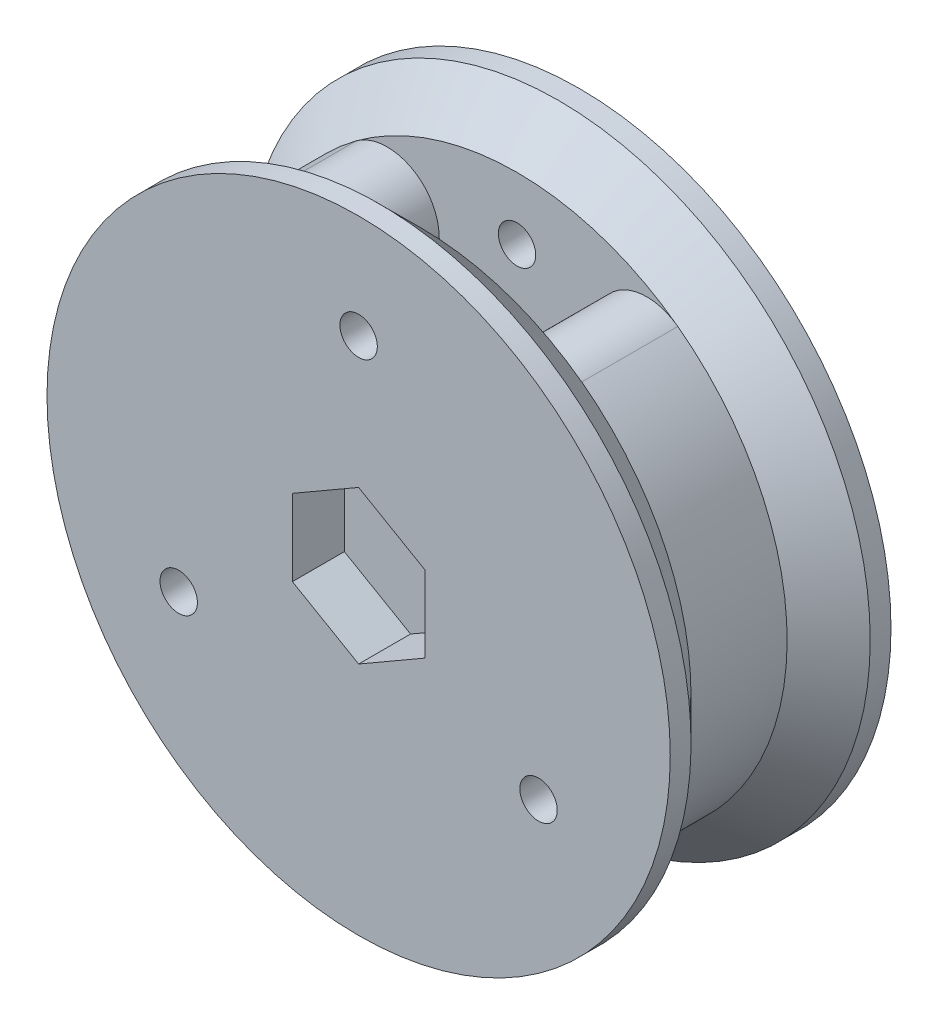
SolidWorks part; units mm, degrees
ref_plane "Front Plane" through (0, 0, 0) normal (0, 0, 1) x (1, 0, 0)
ref_plane "Top Plane" through (0, 0, 0) normal (0, 1, 0) x (1, 0, 0)
ref_plane "Right Plane" through (0, 0, 0) normal (1, 0, 0) x (0, 0, -1)
sketch "Sketch1" plane through (0, 0, 0) normal (0, 0, 1) x (1, 0, 0)
  circle A0 centre (0, 0) radius 30
  dimension "D1" = 60
extrude "Boss-Extrude1" add sketch "Sketch1" along normal blind 21.25
sketch "Sketch2" plane through (0, 0, 21.25) normal (0, 0, 1) x (1, 0, 0)
  line L7 (0, 7.3612) -> (-6.375, 3.6806)
  line L8 (-6.375, 3.6806) -> (-6.375, -3.6806)
  line L9 (-6.375, -3.6806) -> (0, -7.3612)
  line L10 (0, -7.3612) -> (6.375, -3.6806)
  line L11 (6.375, -3.6806) -> (6.375, 3.6806)
  line L12 (6.375, 3.6806) -> (0, 7.3612)
  circle A0 centre (0, 0) radius 6.375 construction
  dimension "D1" = 12.75
extrude "Cut-Extrude1" cut sketch "Sketch2" against normal blind 5
sketch "Sketch4" plane through (0, 0, 0) normal (0, 1, 0) x (1, 0, 0)
  line L0 (30, -19.25) -> (26, -15.25)
  line L1 (30, -21.25) -> (30, 0) construction
  line L2 (26, -15.25) -> (26, -6)
  line L3 (26, -6) -> (30, -2)
  line L4 (30, -2) -> (30, -19.25)
  line L5 (0, 12.6406) -> (0, -40.7984)
  dimension "D1" = 2
  dimension "D2" = 2
  dimension "D3" = 45
  dimension "D4" = 45
  dimension "D5" = 4
revolve "Cut-Revolve1" cut sketch "Sketch4" angle 360 about L5
sketch "Sketch5" plane through (0, 0, 21.25) normal (0, 0, 1) x (1, 0, 0)
  line L0 (0, 0) -> (-17.3205, -10) construction
  line L1 (0, 0) -> (17.3205, -10) construction
  line L2 (0, 0) -> (0, 20) construction
  circle A0 centre (-17.3205, -10) radius 1.8
  circle A2 centre (0, 0) radius 20 construction
  circle A3 centre (17.3205, -10) radius 1.8
  circle A4 centre (0, 20) radius 1.8
  dimension "D1" = 3.6
  dimension "D2" = 40
  dimension "D3" = 120
  dimension "D5" = 3.6
  dimension "D6" = 3.6
  dimension "D4" = 120
extrude "Cut-Extrude2" cut sketch "Sketch5" against normal through all
sketch "Sketch6" plane through (0, 0, 0) normal (0, 0, -1) x (-1, 0, 0)
  line L15 (7.3612, 0) -> (3.6806, 6.375)
  line L16 (3.6806, 6.375) -> (-3.6806, 6.375)
  line L17 (-3.6806, 6.375) -> (-7.3612, 0)
  line L18 (-7.3612, 0) -> (-3.6806, -6.375)
  line L19 (-3.6806, -6.375) -> (3.6806, -6.375)
  line L20 (3.6806, -6.375) -> (7.3612, 0)
  circle A2 centre (0, 0) radius 6.375 construction
  point P1 (0, 6.375)
  dimension "D1" = 12.75
extrude "Cut-Extrude3" cut sketch "Sketch6" against normal blind 13
ref_plane "Plane1" through (0, 40, 0) normal (0, 1, 0) x (1, 0, 0)
sketch "Sketch10" plane through (0, 40, 0) normal (0, 1, 0) x (1, 0, 0)
  line L1 (7.5, -15.25) -> (-7.5, -15.25)
  line L2 (7.5, -15.25) -> (7.5, -6)
  line L3 (7.5, -6) -> (-7.5, -6)
  line L4 (-7.5, -15.25) -> (-7.5, -6)
  line L5 (7.5, -15.25) -> (-7.5, -6) construction
  line L6 (7.5, -6) -> (-7.5, -15.25) construction
  line L8 (-26, -6) -> (26, -6) construction
  line L9 (-26, -15.25) -> (26, -15.25) construction
  point P0 (0, -10.625)
  point P11 (0, -6)
  dimension "D1" = 15
extrude "Cut-Extrude6" cut sketch "Sketch10" against normal blind 28
fillet "Fillet6" radius 5 2 edges at (7.5, 24.8948, 10.625) (-7.5, 24.8948, 10.625)
fillet "Fillet7" radius 5 2 edges at (7.5, 12, 10.625) (-7.5, 12, 10.625)
